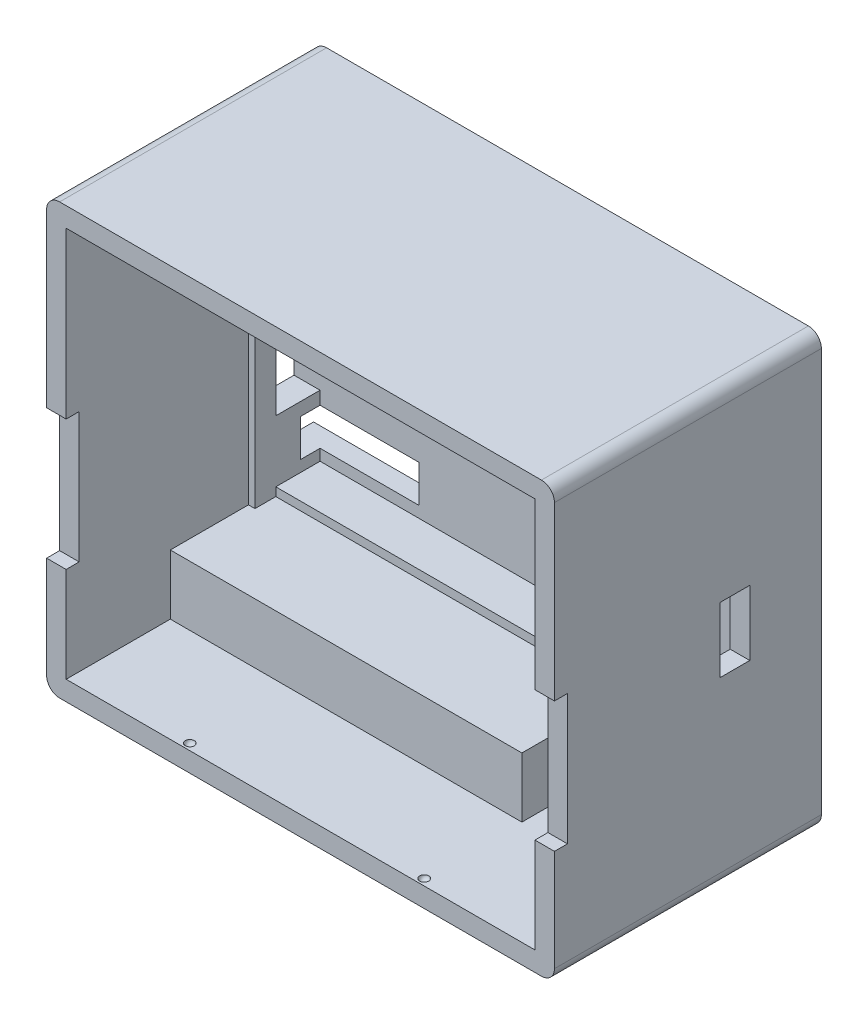
SolidWorks part; units mm, degrees
ref_plane "Plan de face" through (0, 0, 0) normal (1, 0, 0) x (0, 1, 0)
ref_plane "Plan de dessus" through (0, 0, 0) normal (0, 0, 1) x (0, 1, 0)
ref_plane "Plan de droite" through (0, 0, 0) normal (0, 1, 0) x (-1, 0, 0)
sketch "Esquisse1" plane through (0, 0, 0) normal (0, 0, 1) x (0, 1, 0)
  line L0 (0, 19.5) -> (0, -19.5) construction
  line L1 (-16.5, 19.5) -> (16.5, 19.5)
  line L2 (-16.5, 19.5) -> (-16.5, -19.5)
  line L3 (-16.5, -19.5) -> (16.5, -19.5)
  line L4 (16.5, 19.5) -> (16.5, -19.5)
  point P6 (0, 0)
  dimension "D1" = 33
  dimension "D2" = 39
extrude "Boss.-Extru.1" add sketch "Esquisse1" along normal blind 1.5
sketch "Esquisse2" plane through (0, 0, 1.5) normal (0, 0, 1) x (1, 0, 0)
  line L0 (19.5, -16.5) -> (19.5, 16.5) construction
  line L1 (-19.5, 16.5) -> (19.5, 16.5)
  line L2 (-19.5, 16.5) -> (-19.5, -16.5)
  line L3 (-19.5, -16.5) -> (19.5, -16.5)
  line L4 (19.5, 16.5) -> (19.5, -16.5)
  line L6 (-18, 15) -> (18, 15)
  line L7 (-18, 15) -> (-18, -15)
  line L8 (-18, -15) -> (18, -15)
  line L9 (18, 15) -> (18, -15)
  line L11 (-19.5, -16.5) -> (19.5, -16.5) construction
  dimension "D1" = 1.5
  dimension "D2" = 1.5
  dimension "D3" = 1.5
  dimension "D4" = 1.5
extrude "Boss.-Extru.2" add sketch "Esquisse2" along normal blind 19
sketch "Esquisse3" plane through (0, 0, 1.5) normal (0, 0, 1) x (1, 0, 0)
  line L1 (-18, 15) -> (9, 15)
  line L2 (-18, 15) -> (-18, 10.4)
  line L3 (-18, 10.4) -> (9, 10.4)
  line L4 (9, 15) -> (9, 10.4)
  line L5 (-18, 0) -> (18, 0) construction
  line L6 (-18, 15) -> (-18, -15) construction
  line L7 (18, -15) -> (18, 15) construction
  line L12 (-18, -10.4) -> (9, -10.4)
  line L13 (9, -15) -> (9, -10.4)
  line L14 (-18, -15) -> (9, -15)
  line L15 (-18, -15) -> (-18, -10.4)
  dimension "D1" = 4.6
  dimension "D2" = 27
extrude "Boss.-Extru.3" add sketch "Esquisse3" along normal blind 11
sketch "Esquisse5" plane through (0, 0, 1.5) normal (0, 0, 1) x (1, 0, 0)
  line L0 (-18, 10.4) -> (9, 10.4) construction
  line L5 (-18, 10.4) -> (-18, -10.4) construction
  line L11 (8, 10.4) -> (-18, 10.4)
  line L12 (8, 10.4) -> (8, 9.75)
  line L13 (8, 9.75) -> (-18, 9.75)
  line L14 (-18, 10.4) -> (-18, 9.75)
  line L15 (-18, 0) -> (18, 0) construction
  line L16 (-18, 15) -> (-18, -15) construction
  line L17 (18, -15) -> (18, 15) construction
  line L20 (8, -9.75) -> (-18, -9.75)
  line L21 (-18, -10.4) -> (-18, -9.75)
  line L22 (8, -10.4) -> (-18, -10.4)
  line L23 (8, -10.4) -> (8, -9.75)
  dimension "D1" = 0.65
  dimension "D2" = 26
extrude "Boss.-Extru.4" add sketch "Esquisse5" along normal blind 3.4
sketch "Esquisse10" plane through (0, 0, 1.5) normal (0, 0, 1) x (1, 0, 0)
  line L1 (-18, 10.4) -> (-17.5, 10.4)
  line L2 (-18, 10.4) -> (-18, -10.4)
  line L3 (-18, -10.4) -> (-17.5, -10.4)
  line L4 (-17.5, 10.4) -> (-17.5, -10.4)
  line L6 (-18, 10.4) -> (9, 10.4) construction
  line L7 (-17.5, 0) -> (18, 0) construction
  line L8 (8, 10.4) -> (9, 10.4)
  line L9 (8, 10.4) -> (8, 7.4)
  line L10 (8, 7.4) -> (9, 7.4)
  line L11 (9, 10.4) -> (9, 7.4)
  line L12 (18, -15) -> (18, 15) construction
  line L13 (8, -7.4) -> (9, -7.4)
  line L14 (9, -10.4) -> (9, -7.4)
  line L15 (8, -10.4) -> (9, -10.4)
  line L16 (8, -10.4) -> (8, -7.4)
  line L17 (8, 10.4) -> (9, 10.4) construction
  line L18 (-18, 9.75) -> (-18, -9.75) construction
  dimension "D1" = 0.5
  dimension "D2" = 25.5
  dimension "D3" = 1
  dimension "D4" = 3
extrude "Boss.-Extru.5" add sketch "Esquisse10" along normal blind 5
sketch "Esquisse12" plane through (-17.5, 0, 0) normal (1, 0, 0) x (0, 1, 0)
  line L0 (0, 1.5) -> (0, 6.5) construction
  line L1 (-5.025, 1.5) -> (5.025, 1.5)
  line L2 (-5.025, 1.5) -> (-5.025, 4.9)
  line L3 (-5.025, 4.9) -> (5.025, 4.9)
  line L4 (5.025, 1.5) -> (5.025, 4.9)
  line L5 (-5.025, 1.5) -> (5.025, 4.9) construction
  line L6 (-5.025, 4.9) -> (5.025, 1.5) construction
  line L7 (-9.75, 1.5) -> (9.75, 1.5) construction
  line L8 (-10.4, 6.5) -> (10.4, 6.5) construction
  point P0 (0, 3.2)
  dimension "D1" = 3.4
  dimension "D2" = 10.05
extrude "Enlèv. mat.-Extru.5" cut sketch "Esquisse12" against normal through all
sketch "Esquisse13" plane through (-15.6239, 9.1122, 1.5) normal (0, 0, 1) x (1, 0, 0)
  line L0 (33.6239, -9.1122) -> (-1.8761, -9.1122) construction
  line L1 (26.6239, -2.2122) -> (33.6239, -2.2122)
  line L2 (26.6239, -2.2122) -> (26.6239, -16.0122)
  line L3 (26.6239, -16.0122) -> (33.6239, -16.0122)
  line L4 (33.6239, -2.2122) -> (33.6239, -16.0122)
  line L5 (26.6239, -2.2122) -> (33.6239, -16.0122) construction
  line L6 (26.6239, -16.0122) -> (33.6239, -2.2122) construction
  line L7 (33.6239, -24.1122) -> (33.6239, 5.8878) construction
  line L8 (-1.8761, -19.5122) -> (-1.8761, 1.2878) construction
  point P0 (30.1239, -9.1122)
  dimension "D1" = 13.8
  dimension "D2" = 7
extrude "Boss.-Extru.6" add sketch "Esquisse13" along normal blind 5.4
sketch "Esquisse14" plane through (0, 0, 6.9) normal (0, 0, 1) x (1, 0, 0)
  line L0 (18, -6.9) -> (18, 6.9) construction
  line L1 (12, 5.9) -> (18, 5.9)
  line L2 (12, 5.9) -> (12, -5.9)
  line L3 (12, -5.9) -> (18, -5.9)
  line L4 (18, 5.9) -> (18, -5.9)
  line L5 (11, 6.9) -> (11, -6.9) construction
  line L6 (11, -6.9) -> (18, -6.9) construction
  line L7 (18, 6.9) -> (11, 6.9) construction
  dimension "D1" = 1
  dimension "D2" = 1
  dimension "D3" = 1
extrude "Enlèv. mat.-Extru.6" cut sketch "Esquisse14" against normal blind 2
sketch "Esquisse15" plane through (18, 0, 0) normal (-1, 0, 0) x (0, -1, 0)
  line L0 (0, 4.9) -> (0, 20.5) construction
  line L1 (-2.5, 7.8) -> (2.5, 7.8)
  line L2 (-2.5, 7.8) -> (-2.5, 5.5)
  line L3 (-2.5, 5.5) -> (2.5, 5.5)
  line L4 (2.5, 7.8) -> (2.5, 5.5)
  line L5 (-2.5, 7.8) -> (2.5, 5.5) construction
  line L6 (-2.5, 5.5) -> (2.5, 7.8) construction
  line L7 (5.9, 4.9) -> (-5.9, 4.9) construction
  line L8 (15, 20.5) -> (-15, 20.5) construction
  point P0 (0, 6.65)
  dimension "D1" = 2.3
  dimension "D2" = 5
  dimension "D3" = 0.6
extrude "Enlèv. mat.-Extru.7" cut sketch "Esquisse15" against normal through all
ref_plane "Plan1" through (0, 14.96, 0) normal (0, -1, 0) x (-1, 0, 0)
sketch "Esquisse16" plane through (0, 14.96, 0) normal (0, -1, 0) x (1, 0, 0)
  line L0 (-14.897, 20) -> (16.1051, 20) construction
  line L1 (18, 20.5) -> (-18, 20.5) construction
  line L2 (-18, 20.5) -> (-18, 12.5) construction
  line L3 (-8.65, 20) -> (-9.35, 20)
  arc A0 (-8.65, 20) -> (-9.35, 20) centre (-9, 20) ccw
  dimension "D2" = 0.7
  dimension "D1" = 0.5
  dimension "D3" = 9
revolve "Enlèvement de matière-Révolution5" cut sketch "Esquisse16" angle 180 about L0
mirror "Symétrie3" about plane through (0, 0, 0) normal (0, 1, 0) of "Enlèvement de matière-Révolution5"
mirror "Symétrie4" about plane through (0, 0, 0) normal (1, 0, 0) of "Enlèvement de matière-Révolution5", "Symétrie3"
sketch "Esquisse17" plane through (-19.5, 0, 0) normal (-1, 0, 0) x (0, -1, 0)
  line L0 (0, 1.5) -> (2.6214, 19.5) construction
  line L1 (-2.3058, 20.5) -> (7.6942, 20.5)
  line L2 (-2.3058, 20.5) -> (-2.3058, 19.5)
  line L3 (-2.3058, 19.5) -> (7.6942, 19.5)
  line L4 (7.6942, 20.5) -> (7.6942, 19.5)
  line L5 (-2.3058, 20.5) -> (7.6942, 19.5) construction
  line L6 (-2.3058, 19.5) -> (7.6942, 20.5) construction
  line L7 (16.5814, 19.5) -> (-11.3386, 19.5) construction
  line L8 (5.025, 1.5) -> (-5.025, 1.5) construction
  line L9 (18.1214, 20.5) -> (-12.8786, 20.5) construction
  point P0 (2.6942, 20)
  dimension "D1" = 10
  dimension "D2" = 1
extrude "Enlèv. mat.-Extru.8" cut sketch "Esquisse17" against normal through all
fillet "Congé1" radius 1 4 edges at (19.5, 16.5, 10.25) (19.5, -16.5, 10.25) (-19.5, 16.5, 10.25) (-19.5, -16.5, 10.25)
sketch "Esquisse18" plane through (0, 0, 1.5) normal (0, 0, 1) x (1, 0, 0)
  line L0 (11, 0) -> (-17.5, 0) construction
  line L1 (-17.5, 6.025) -> (-9.9042, 6.025)
  line L2 (-17.5, 6.025) -> (-17.5, 8.8859)
  line L3 (-17.5, 8.8859) -> (-9.9042, 8.8859)
  line L4 (-9.9042, 6.025) -> (-9.9042, 8.8859)
  line L5 (11, 6.9) -> (11, -6.9) construction
  line L6 (-17.5, -10.4) -> (-17.5, 10.4) construction
  line L7 (-17.5, -8.8859) -> (-9.9042, -8.8859)
  line L8 (-9.9042, -6.025) -> (-9.9042, -8.8859)
  line L9 (-17.5, -6.025) -> (-9.9042, -6.025)
  line L10 (-17.5, -6.025) -> (-17.5, -8.8859)
  line L11 (-17.5, 5.025) -> (-17.5, 9.75) construction
  line L13 (-19.5, 5.025) -> (-17.5, 5.025) construction
  dimension "D1" = 2.8609
  dimension "D2" = 7.5958
  dimension "D3" = 1
extrude "Enlèv. mat.-Extru.9" cut sketch "Esquisse18" against normal through all
sketch "Esquisse19" plane through (-17.5, 0, 0) normal (1, 0, 0) x (0, 1, 0)
  line L0 (-6.025, 0) -> (-6.025, 1.5) construction
  line L1 (-8.8859, 3) -> (-6.025, 3)
  line L2 (-8.8859, 3) -> (-8.8859, 0)
  line L3 (-8.8859, 0) -> (-6.025, 0)
  line L4 (-6.025, 3) -> (-6.025, 0)
  line L5 (-8.8859, 0) -> (-8.8859, 1.5) construction
  line L6 (-6.025, 0) -> (-8.8859, 0) construction
  line L7 (0, 4.9) -> (0, 6.5) construction
  line L8 (5.025, 4.9) -> (-5.025, 4.9) construction
  line L9 (-10.4, 6.5) -> (10.4, 6.5) construction
  line L10 (8.8859, 0) -> (6.025, 0)
  line L11 (6.025, 3) -> (6.025, 0)
  line L12 (8.8859, 3) -> (6.025, 3)
  line L13 (8.8859, 3) -> (8.8859, 0)
  dimension "D1" = 3
extrude "Enlèv. mat.-Extru.10" cut sketch "Esquisse19" against normal through all
